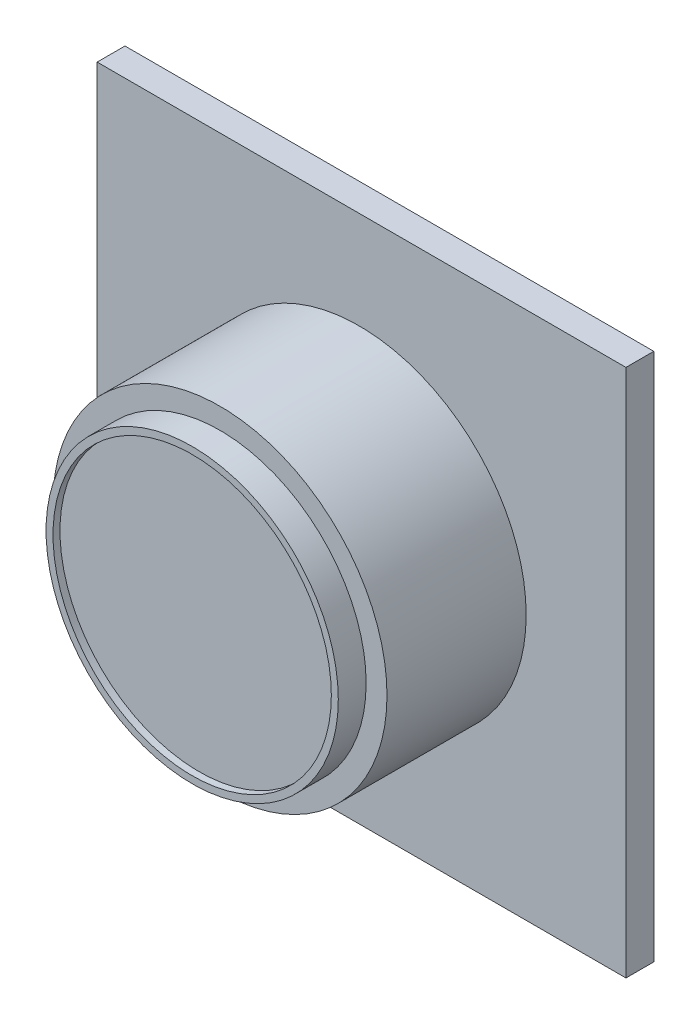
SolidWorks part; units mm, degrees
ref_plane "Front Plane" through (0, 0, 0) normal (0, 0, 1) x (1, 0, 0)
ref_plane "Top Plane" through (0, 0, 0) normal (0, 1, 0) x (1, 0, 0)
ref_plane "Right Plane" through (0, 0, 0) normal (1, 0, 0) x (0, 0, -1)
sketch "Sketch1" plane through (0, 0, 0) normal (0, 0, 1) x (1, 0, 0)
  line L1 (-9.4144, 9.5) -> (9.5856, 9.5)
  line L2 (-9.4144, 9.5) -> (-9.4144, -9.5)
  line L3 (-9.4144, -9.5) -> (9.5856, -9.5)
  line L4 (9.5856, 9.5) -> (9.5856, -9.5)
  point P4 (-9.4144, 0)
  dimension "D1" = 19
  dimension "D2" = 19
extrude "Boss-Extrude1" add sketch "Sketch1" along normal blind 1
sketch "Sketch2" plane through (0, 0, 1) normal (0, 0, 1) x (1, 0, 0)
  circle A0 centre (0, 0) radius 6
  dimension "D1" = 12
extrude "Boss-Extrude2" add sketch "Sketch2" along normal blind 5
sketch "Sketch3" plane through (0, 0, 6) normal (0, 0, 1) x (1, 0, 0)
  circle A0 centre (0, 0) radius 5.25
  circle A1 centre (0, 0) radius 5
  dimension "D1" = 10.5
  dimension "D2" = 10
extrude "Boss-Extrude5" add sketch "Sketch3" along normal blind 1
sketch "Sketch6" plane through (0, 0, 7) normal (0, 0, 1) x (1, 0, 0)
  circle A0 centre (0, 0) radius 5
extrude "Cut-Extrude3" cut sketch "Sketch6" against normal through all
sketch "Sketch7" plane through (0, 0, 6) normal (0, 0, 1) x (1, 0, 0)
  circle A0 centre (0, 0) radius 5.25
extrude "Boss-Extrude6" add sketch "Sketch7" along normal blind 0.75
